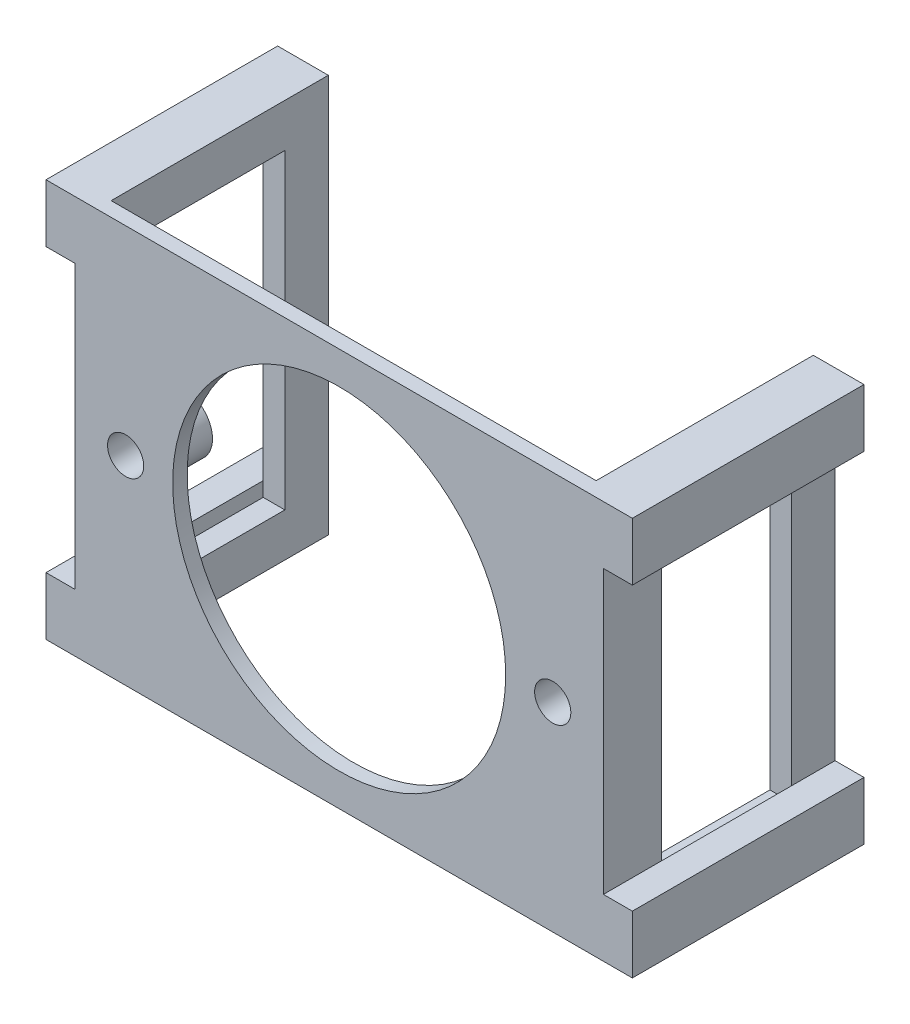
SolidWorks part; units mm, degrees
ref_plane "Front Plane" through (0, 0, 0) normal (0, 0, 1) x (1, 0, 0)
ref_plane "Top Plane" through (0, 0, 0) normal (0, 1, 0) x (1, 0, 0)
ref_plane "Right Plane" through (0, 0, 0) normal (1, 0, 0) x (0, 0, -1)
sketch "Sketch2" plane through (0, 0, 0) normal (0, 0, 1) x (1, 0, 0)
  line L0 (-18.25, 13.75) -> (-18.25, -13.75)
  line L1 (-16.25, 11.75) -> (16.25, 11.75) construction
  line L2 (-16.25, 11.75) -> (-16.25, -11.75) construction
  line L3 (-16.25, -11.75) -> (16.25, -11.75) construction
  line L4 (16.25, 11.75) -> (16.25, -11.75) construction
  line L5 (-16.25, 11.75) -> (16.25, -11.75) construction
  line L6 (-16.25, -11.75) -> (16.25, 11.75) construction
  line L7 (-18.25, -13.75) -> (18.25, -13.75)
  line L8 (18.25, 13.75) -> (18.25, -13.75)
  line L9 (-18.25, 13.75) -> (18.25, 13.75)
  line L10 (-18.25, 0) -> (18.25, 0) construction
  circle A0 centre (0, 0) radius 11.5
  circle A1 centre (-14.75, 0) radius 1.25
  circle A3 centre (14.75, 0) radius 1.25
  point P0 (0, 0)
  dimension "D1" = 23
  dimension "D5" = 2.5
  dimension "D6" = 1.5
  dimension "D2" = 32.5
  dimension "D3" = 23.5
  dimension "D7" = 1.5
  dimension "D4" = 2
extrude "Boss-Extrude1" add sketch "Sketch2" against normal blind 1
sketch "Sketch4" plane through (0, 0, -1) normal (0, 0, -1) x (-1, 0, 0)
  line L0 (-16.75, 13.75) -> (-16.75, 4)
  line L1 (-18.25, 13.75) -> (18.25, 13.75) construction
  line L2 (18.25, -13.75) -> (-18.25, -13.75) construction
  line L3 (-18.25, -13.75) -> (-18.25, 13.75) construction
  line L4 (-16.75, 13.75) -> (-18.25, 13.75)
  line L5 (-18.25, 13.75) -> (-18.25, -13.75)
  line L6 (-18.25, -13.75) -> (-16.75, -13.75)
  line L7 (-16.75, -4) -> (-16.75, -13.75)
  arc A0 (-14.75, -2) -> (-14.75, 2) centre (-14.75, 0) ccw
  arc A1 (-14.75, -2) -> (-16.75, -4) centre (-14.75, -4) ccw
  arc A2 (-16.75, 4) -> (-14.75, 2) centre (-14.75, 4) ccw
  circle A4 centre (-14.75, 0) radius 1.25 construction
  circle A5 centre (-14.75, 0) radius 1.25
  dimension "D1" = 1.5
extrude "Boss-Extrude2" add sketch "Sketch4" along normal blind 3 contours A2 A0 A1 L7 L6 L5 L4 L0
sketch "Sketch5" plane through (0, 0, -4) normal (0, 0, -1) x (-1, 0, 0)
  line L1 (-18.25, 13.75) -> (-16.75, 13.75)
  line L2 (-18.25, 13.75) -> (-18.25, -13.75)
  line L3 (-18.25, -13.75) -> (-16.75, -13.75)
  line L4 (-16.75, 13.75) -> (-16.75, -13.75)
extrude "Boss-Extrude3" add sketch "Sketch5" along normal blind 12
sketch "Sketch6" plane through (18.25, 0, 0) normal (1, 0, 0) x (0, 0, -1)
  line L4 (16, -13.75) -> (0, -13.75) construction
  line L5 (16, 13.75) -> (1, 13.75)
  line L6 (16, 13.75) -> (16, -13.75)
  line L7 (16, -13.75) -> (1, -13.75)
  line L8 (1, 13.75) -> (1, -13.75)
  line L10 (4, -4) -> (4, 4) construction
  line L11 (13, 10.75) -> (13, -10.75)
  line L12 (13, -10.75) -> (4, -10.75)
  line L13 (4, 10.75) -> (4, -10.75)
  line L14 (13, 10.75) -> (4, 10.75)
  dimension "D1" = 3
  dimension "D2" = 3
extrude "Cut-Extrude1" cut sketch "Sketch6" against normal up to surface (1.5 mm away) contours L11 L12 L13 L14 up to face at (16.75, 0, -5.5)
sketch "Sketch7" plane through (0, 0, -16) normal (0, 0, -1) x (-1, 0, 0)
  line L0 (-18.25, 13.75) -> (-20.25, 13.75)
  line L1 (-18.25, 13.75) -> (-18.25, -13.75) construction
  line L2 (-20.25, 13.75) -> (-20.25, 9.75)
  line L3 (-20.25, 9.75) -> (-18.25, 9.75)
  line L4 (-18.25, 9.75) -> (-18.25, 13.75)
  line L6 (55, 0) -> (-55, 0) construction
  line L7 (-20.25, -9.75) -> (-18.25, -9.75)
  line L8 (-20.25, -13.75) -> (-20.25, -9.75)
  line L9 (-18.25, -13.75) -> (-20.25, -13.75)
  line L10 (-18.25, -9.75) -> (-18.25, -13.75)
  point P4 (0, 0)
  dimension "D1" = 4
  dimension "D2" = 2
extrude "Boss-Extrude4" add sketch "Sketch7" against normal up to surface (16 mm away) up to face at (16, 0, 0)
mirror "Mirror1" about plane through (0, 0, 0) normal (1, 0, 0) of "Boss-Extrude2", "Boss-Extrude4", "Cut-Extrude1", "Boss-Extrude3"
